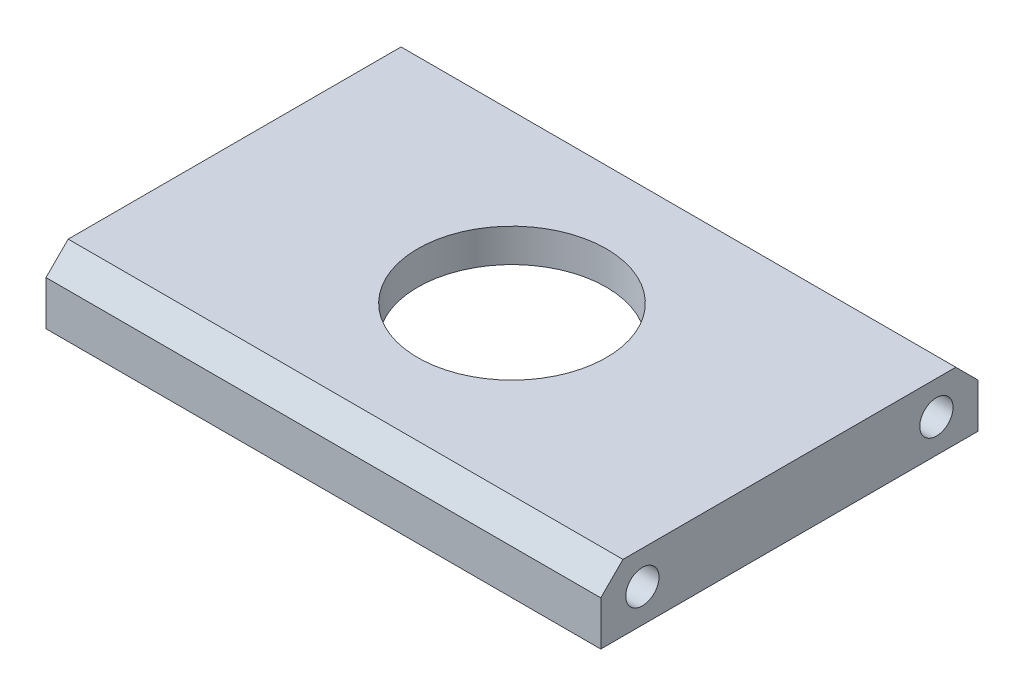
SolidWorks part; units mm, degrees
ref_plane "Front Plane" through (0, 0, 0) normal (0, 0, 1) x (1, 0, 0)
ref_plane "Top Plane" through (0, 0, 0) normal (0, 1, 0) x (1, 0, 0)
ref_plane "Right Plane" through (0, 0, 0) normal (1, 0, 0) x (0, 0, -1)
sketch "Sketch1" plane through (0, 0, 0) normal (0, 1, 0) x (1, 0, 0)
  line L1 (0, 0) -> (50, 0)
  line L2 (0, 0) -> (0, 34)
  line L3 (0, 34) -> (50, 34)
  line L4 (50, 0) -> (50, 34)
  dimension "D1" = 34
  dimension "D2" = 50
extrude "Boss-Extrude1" add sketch "Sketch1" along normal blind 6
sketch "Sketch2" plane through (50, 0, 0) normal (1, 0, 0) x (0, 0, -1)
  line L0 (0, 3) -> (3.75, 3) construction
  line L1 (0, 6) -> (0, 0) construction
  line L2 (34, 3) -> (30.25, 3) construction
  line L3 (34, 6) -> (34, 0) construction
  circle A0 centre (3.75, 3) radius 1.5
  circle A1 centre (30.25, 3) radius 1.5
  dimension "D1" = 3.75
  dimension "D2" = 3.75
extrude "Cut-Extrude1" cut sketch "Sketch2" against normal blind 7
sketch "Sketch3" plane through (0, 0, 0) normal (-1, 0, 0) x (0, 0, 1)
  line L0 (-34, 3) -> (-30.25, 3) construction
  line L1 (-34, 6) -> (-34, 0) construction
  line L2 (0, 3) -> (-3.75, 3) construction
  line L3 (0, 6) -> (0, 0) construction
  circle A0 centre (-30.25, 3) radius 1.5
  circle A1 centre (-3.75, 3) radius 1.5
  dimension "D1" = 3.75
  dimension "D2" = 3.75
extrude "Cut-Extrude2" cut sketch "Sketch3" against normal blind 7
chamfer "Chamfer1" distance 2 angle 45 2 edges at (25, 6, -34) (25, 6, 0)
sketch "Sketch4" plane through (0, 0, 0) normal (0, -1, 0) x (1, 0, 0)
  line L0 (25, 0) -> (25, -34) construction
  line L1 (0, 0) -> (50, 0) construction
  line L2 (50, -34) -> (0, -34) construction
  circle A0 centre (25, -17) radius 15
extrude "Cut-Extrude3" cut sketch "Sketch4" against normal blind 3
sketch "Sketch5" plane through (0, 3, 0) normal (0, -1, 0) x (1, 0, 0)
  circle A0 centre (25, -17) radius 8.5
extrude "Cut-Extrude4" cut sketch "Sketch5" against normal blind 3
